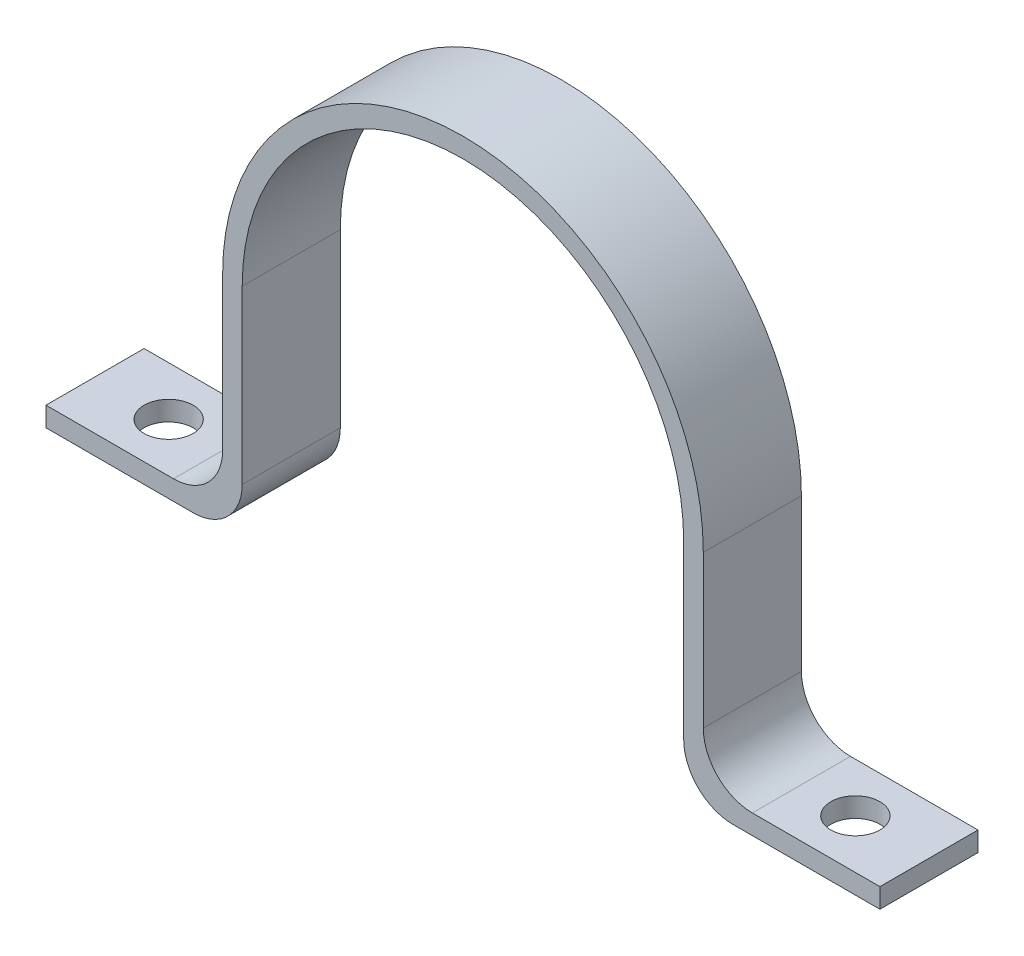
SolidWorks part; units mm, degrees
ref_plane "Front Plane" through (0, 0, 0) normal (0, 0, 1) x (1, 0, 0)
ref_plane "Top Plane" through (0, 0, 0) normal (0, 1, 0) x (1, 0, 0)
ref_plane "Right Plane" through (0, 0, 0) normal (1, 0, 0) x (0, 0, -1)
sketch "Sketch2" plane through (0, 0, 0) normal (0, 0, 1) x (1, 0, 0)
  line L0 (24.5, -20.5) -> (32.5, -20.5)
  line L1 (32.5, -20.5) -> (32.5, -22.5)
  line L3 (-24.5, 0) -> (-24.5, -20.5)
  line L4 (-22.5, 0) -> (-22.5, -22.5)
  line L5 (22.5, 0) -> (22.5, -22.5)
  line L6 (24.5, 0) -> (24.5, -20.5)
  line L9 (22.5, -22.5) -> (32.5, -22.5)
  line L10 (-22.5, -22.5) -> (-32.5, -22.5)
  line L11 (-22.5, -22.5) -> (22.5, -22.5) construction
  line L12 (22.5, -22.5) -> (32.5, -22.5) construction
  line L13 (-32.5, -22.5) -> (-32.5, -20.5)
  line L14 (0, 22.5) -> (0, 61.5689) construction
  line L15 (-32.5, -20.5) -> (-24.5, -20.5)
  arc A2 (22.5, 0) -> (-22.5, 0) centre (0, 0) ccw
  arc A3 (24.5, 0) -> (-24.5, 0) centre (0, 0) ccw
  point P6 (0, -21.5)
  point P9 (0, -21.5)
  point P11 (0, -21.5)
  point P12 (0, -21.5)
  dimension "D1" = 22.5
  dimension "D2" = 24.5
  dimension "D3" = 2
  dimension "D4" = 2
  dimension "D5" = 10
  dimension "D6" = 10
  dimension "D7" = 22.5
  dimension "D8" = 22.5
extrude "Boss-Extrude1" add sketch "Sketch2" along normal blind 10
fillet "Fillet11" radius 5 1 edges at (-22.5, -22.5, 5)
fillet "Fillet12" radius 5 1 edges at (-24.5, -20.5, 5)
fillet "Fillet13" radius 5 2 edges at (24.5, -20.5, 5) (22.5, -22.5, 5)
sketch "Sketch7" plane through (32.5, 0, 0) normal (1, 0, 0) x (0, 0, -1)
  line L1 (-10, -20.5) -> (0, -20.5)
  line L2 (-10, -20.5) -> (-10, -22.5)
  line L3 (-10, -22.5) -> (0, -22.5)
  line L4 (0, -20.5) -> (0, -22.5)
extrude "Boss-Extrude5" add sketch "Sketch7" along normal blind 10
sketch "Sketch8" plane through (-32.5, 0, 0) normal (-1, 0, 0) x (0, 0, 1)
  line L1 (10, -20.5) -> (0, -20.5)
  line L2 (10, -20.5) -> (10, -22.5)
  line L3 (10, -22.5) -> (0, -22.5)
  line L4 (0, -20.5) -> (0, -22.5)
extrude "Boss-Extrude6" add sketch "Sketch8" along normal blind 10
sketch "Sketch9" plane through (0, -20.5, 0) normal (0, 1, 0) x (1, 0, 0)
  circle A0 centre (-35, -5) radius 2.5
extrude "Cut-Extrude2" cut sketch "Sketch9" against normal blind 10
mirror "Mirror2" about plane through (0, 0, 0) normal (1, 0, 0) of "Cut-Extrude2"
